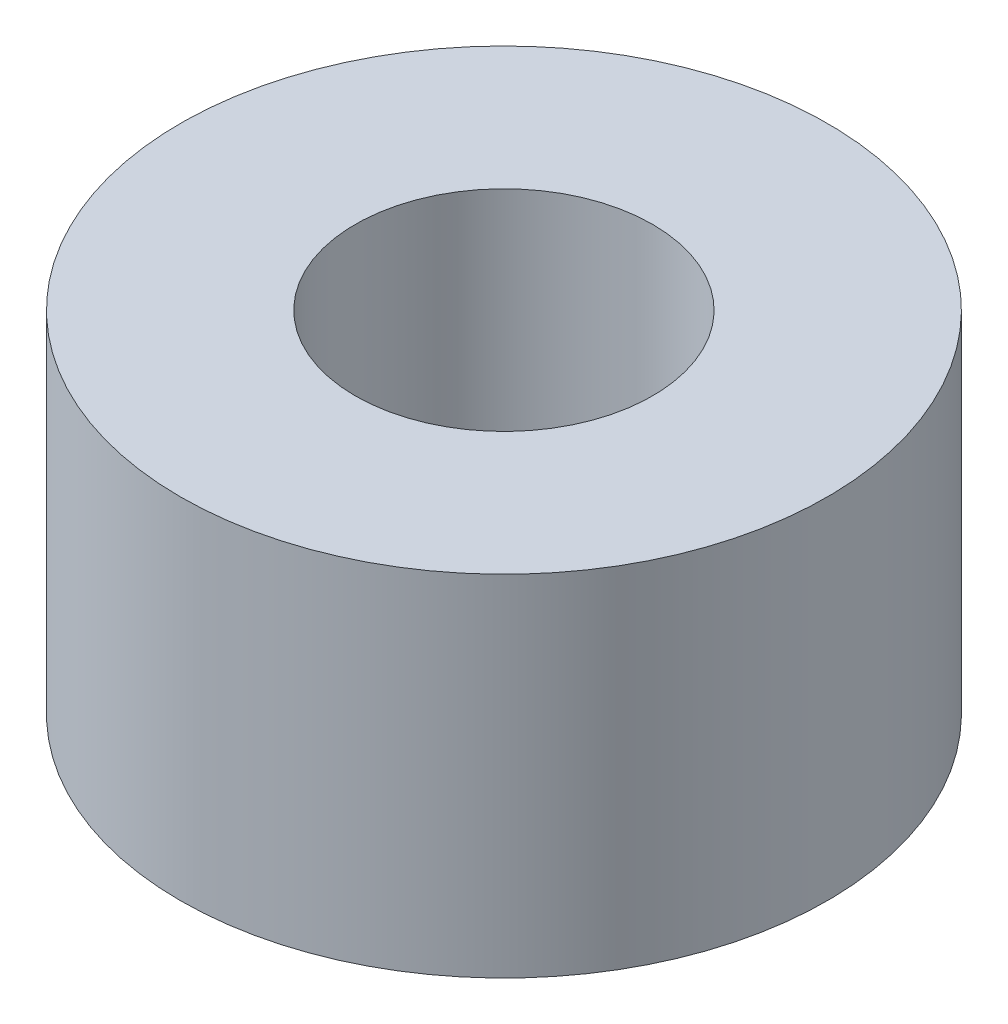
SolidWorks part; units mm, degrees
ref_plane "Front Plane" through (0, 0, 0) normal (0, 0, 1) x (1, 0, 0)
ref_plane "Top Plane" through (0, 0, 0) normal (0, 1, 0) x (1, 0, 0)
ref_plane "Right Plane" through (0, 0, 0) normal (1, 0, 0) x (0, 0, -1)
sketch "Sketch2" plane through (0, 0, 0) normal (0, 1, 0) x (1, 0, 0)
  circle A0 centre (0, 0) radius 2.159
  circle A1 centre (0, 0) radius 4.699
  dimension "D1" = 4.318
  dimension "D2" = 2.54
extrude "Boss-Extrude1" add sketch "Sketch2" along normal blind 5.08
